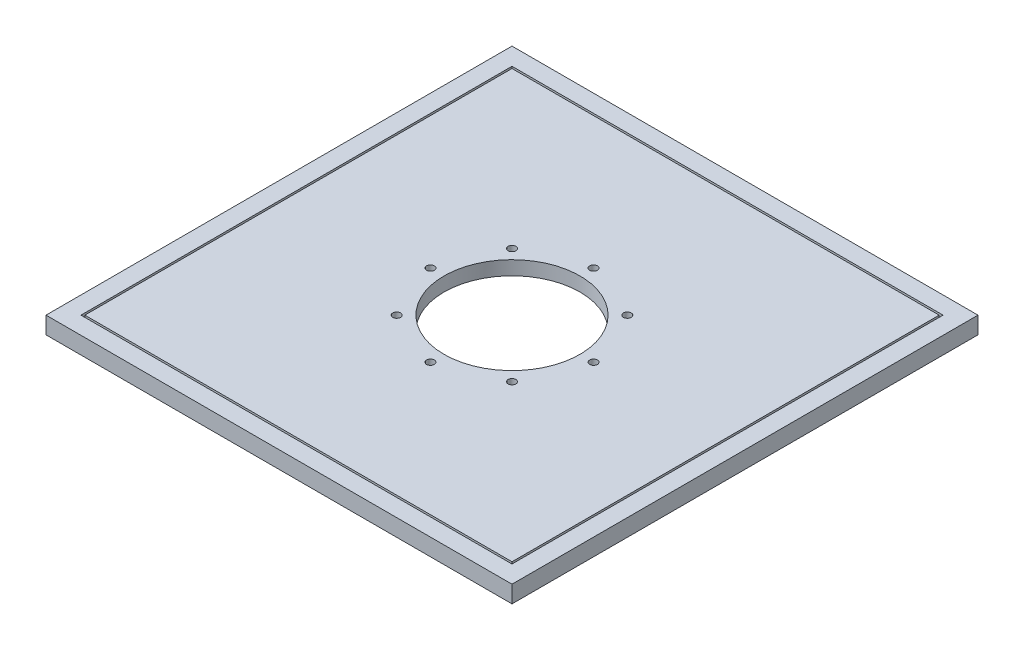
SolidWorks part; units mm, degrees
ref_plane "Front Plane" through (0, 0, 0) normal (0, 0, 1) x (1, 0, 0)
ref_plane "Top Plane" through (0, 0, 0) normal (0, 1, 0) x (1, 0, 0)
ref_plane "Right Plane" through (0, 0, 0) normal (1, 0, 0) x (0, 0, -1)
sketch "Sketch1" plane through (0, 0, 0) normal (0, 1, 0) x (1, 0, 0)
  line L1 (-300, 300) -> (300, 300)
  line L2 (-300, 300) -> (-300, -300)
  line L3 (-300, -300) -> (300, -300)
  line L4 (300, 300) -> (300, -300)
  line L5 (-300, 300) -> (300, -300) construction
  line L6 (-300, -300) -> (300, 300) construction
  point P0 (0, 0)
  dimension "D1" = 600
  dimension "600" = 600
extrude "plate" add sketch "Sketch1" along normal blind 22
sketch "Sketch2" plane through (0, 22, 0) normal (0, 1, 0) x (1, 0, 0)
  circle A0 centre (0, 0) radius 87.5
  dimension "D1" = 175
extrude "bearing-hole" cut sketch "Sketch2" against normal through all
sketch "Sketch4" plane through (0, 22, 0) normal (0, 1, 0) x (1, 0, 0)
  line L1 (-277.5, 277.5) -> (277.5, 277.5)
  line L2 (-277.5, 277.5) -> (-277.5, -277.5)
  line L3 (-277.5, -277.5) -> (277.5, -277.5)
  line L4 (277.5, 277.5) -> (277.5, -277.5)
  line L5 (-277.5, 277.5) -> (277.5, -277.5) construction
  line L6 (-277.5, -277.5) -> (277.5, 277.5) construction
  line L7 (-275, 275) -> (275, 275)
  line L8 (-275, 275) -> (-275, -275)
  line L9 (-275, -275) -> (275, -275)
  line L10 (275, 275) -> (275, -275)
  line L11 (-275, 275) -> (275, -275) construction
  line L12 (-275, -275) -> (275, 275) construction
  point P0 (0, 0)
  point P6 (0, 0)
  dimension "D1" = 550
  dimension "D2" = 550
  dimension "D3" = 555
extrude "Cut-Extrude3" cut sketch "Sketch4" against normal blind 10
sketch "Sketch5" plane through (0, 0, 0) normal (0, -1, 0) x (1, 0, 0)
  circle A0 centre (0, 0) radius 125
  dimension "D1" = 250
extrude "Cut-Extrude4" cut sketch "Sketch5" against normal blind 4
sketch "Sketch6" plane through (0, 4, 0) normal (0, -1, 0) x (1, 0, 0)
  circle A0 centre (0, 105) radius 5
  circle A1 centre (74.2462, 74.2462) radius 5
  circle A2 centre (105, 0) radius 5
  circle A3 centre (74.2462, -74.2462) radius 5
  circle A4 centre (0, -105) radius 5
  circle A5 centre (-74.2462, -74.2462) radius 5
  circle A6 centre (-105, 0) radius 5
  circle A7 centre (-74.2462, 74.2462) radius 5
  point P19 (0, 0)
  dimension "D1" = 10
  dimension "D2" = 105
  dimension "D3" = 8
extrude "Cut-Extrude5" cut sketch "Sketch6" against normal through all
